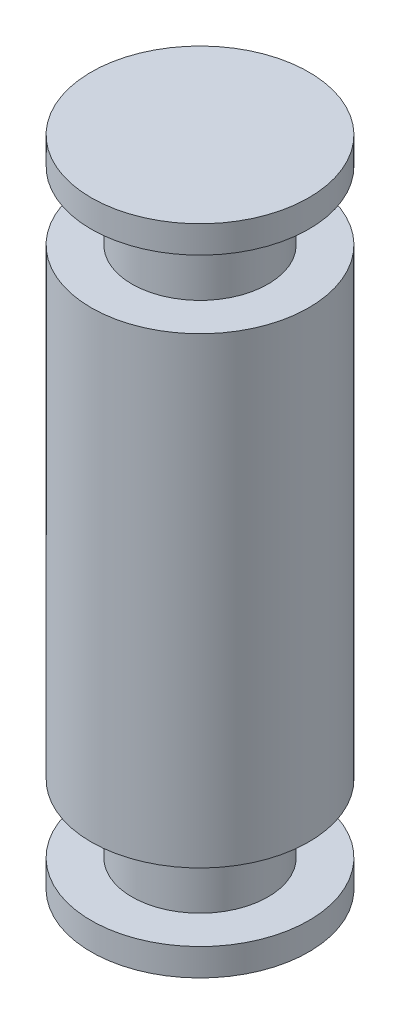
SolidWorks part; units mm, degrees
material "Titanium"
ref_plane "Front Plane" through (0, 0, 0) normal (0, 0, 1) x (1, 0, 0)
ref_plane "Top Plane" through (0, 0, 0) normal (0, 1, 0) x (1, 0, 0)
ref_plane "Right Plane" through (0, 0, 0) normal (1, 0, 0) x (0, 0, -1)
sketch "Sketch1" plane through (0, 0, 0) normal (0, 1, 0) x (1, 0, 0)
  circle A0 centre (0, 0) radius 4
extrude "Boss-Extrude1" add sketch "Sketch1" along normal blind 17
sketch "Sketch2" plane through (0, 0, 0) normal (0, -1, 0) x (1, 0, 0)
  circle A0 centre (0, 0) radius 2.5
extrude "Boss-Extrude2" add sketch "Sketch2" along normal blind 2.5
sketch "Sketch3" plane through (0, -2.5, 0) normal (0, -1, 0) x (1, 0, 0)
  circle A0 centre (0, 0) radius 4
extrude "Boss-Extrude3" add sketch "Sketch3" along normal blind 1
sketch "Sketch4" plane through (0, 17, 0) normal (0, 1, 0) x (1, 0, 0)
  circle A0 centre (0, 0) radius 2.5
extrude "Boss-Extrude4" add sketch "Sketch4" along normal blind 2.5
sketch "Sketch5" plane through (0, 19.5, 0) normal (0, 1, 0) x (1, 0, 0)
  circle A0 centre (0, 0) radius 4
extrude "Boss-Extrude5" add sketch "Sketch5" along normal blind 1
